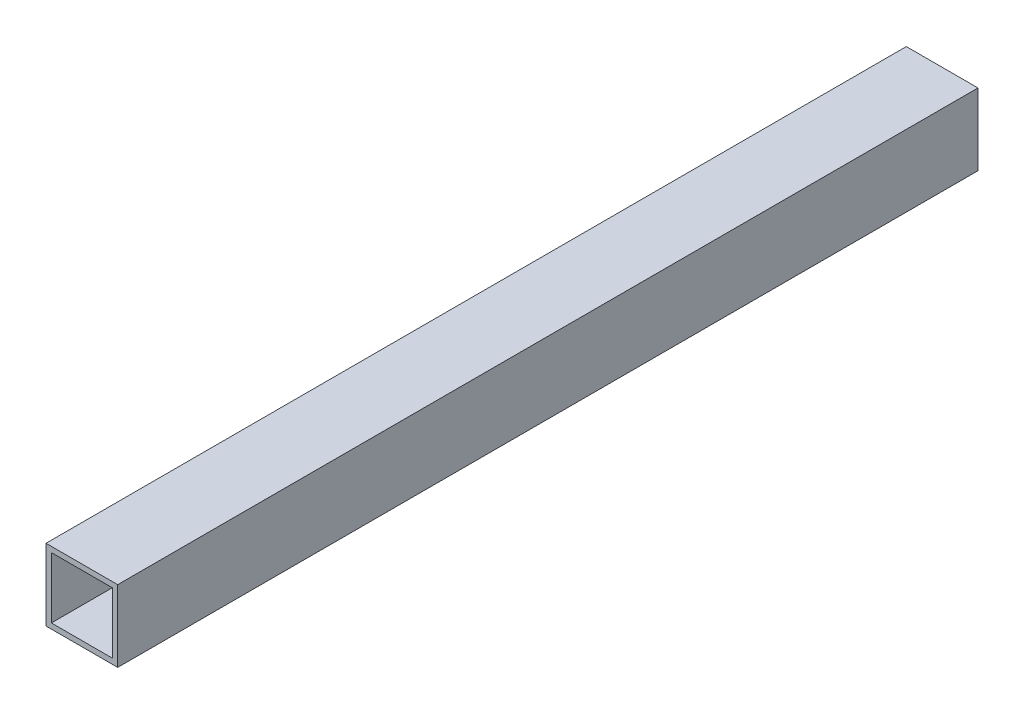
SolidWorks part; units mm, degrees
material "6063-T6"
ref_plane "Płaszczyzna przednia" through (0, 0, 0) normal (0, 0, 1) x (1, 0, 0)
ref_plane "Płaszczyzna górna" through (0, 0, 0) normal (0, 1, 0) x (1, 0, 0)
ref_plane "Płaszczyzna prawa" through (0, 0, 0) normal (1, 0, 0) x (0, 0, -1)
sketch "Szkic1" plane through (0, 0, 0) normal (0, 0, 1) x (1, 0, 0)
  line L0 (8.5, 8.5) -> (-8.5, 8.5)
  line L1 (10, -10) -> (-10, -10)
  line L2 (10, -10) -> (10, 10)
  line L3 (10, 10) -> (-10, 10)
  line L4 (-10, -10) -> (-10, 10)
  line L5 (10, -10) -> (-10, 10) construction
  line L6 (10, 10) -> (-10, -10) construction
  line L7 (-8.5, -8.5) -> (-8.5, 8.5)
  line L8 (8.5, -8.5) -> (-8.5, -8.5)
  line L9 (8.5, -8.5) -> (8.5, 8.5)
  point P0 (0, 0)
  dimension "D1" = 20
  dimension "D2" = 20
  dimension "D3" = 1.5
extrude "Dodanie-wyciągnięcie1" add sketch "Szkic1" along normal blind 240
